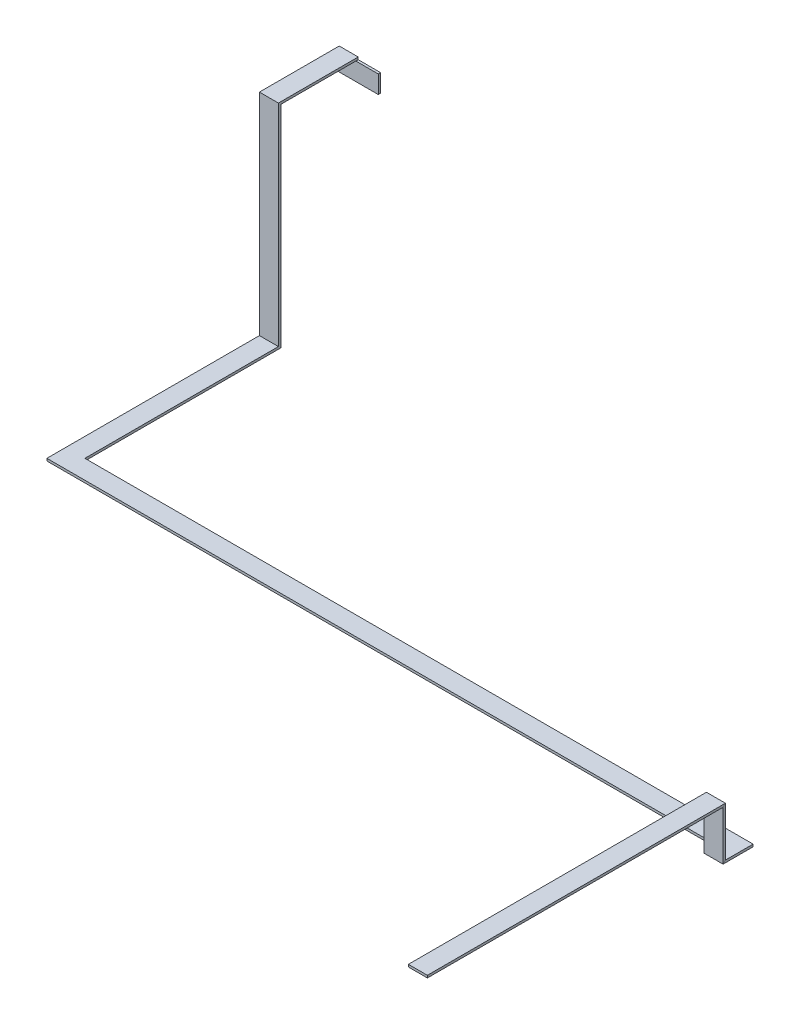
SolidWorks part; units mm, degrees
ref_plane "Alzado" through (0, 0, 0) normal (0, 0, 1) x (1, 0, 0)
ref_plane "Planta" through (0, 0, 0) normal (0, 1, 0) x (1, 0, 0)
ref_plane "Vista lateral" through (0, 0, 0) normal (1, 0, 0) x (0, 0, -1)
sketch "Croquis2" plane through (0, 0, 0) normal (0, 0, 1) x (1, 0, 0)
  line L1 (-25.4, 285.195) -> (25.4, 285.195)
  line L2 (-25.4, 285.195) -> (-25.4, -285.195)
  line L3 (-25.4, -285.195) -> (25.4, -285.195)
  line L4 (25.4, 285.195) -> (25.4, -285.195)
  line L5 (-25.4, 285.195) -> (25.4, -285.195) construction
  line L6 (-25.4, -285.195) -> (25.4, 285.195) construction
  point P0 (0, 0)
  dimension "D1" = 570.39
  dimension "D2" = 50.8
extrude "Saliente-Extruir1" add sketch "Croquis2" along normal blind 6.31
sketch "Croquis3" plane through (0, 0, 6.31) normal (0, 0, 1) x (1, 0, 0)
  line L1 (-25.4, -278.885) -> (25.4, -278.885)
  line L2 (-25.4, -278.885) -> (-25.4, -285.195)
  line L3 (-25.4, -285.195) -> (25.4, -285.195)
  line L4 (25.4, -278.885) -> (25.4, -285.195)
  line L5 (-25.4, -278.885) -> (25.4, -285.195) construction
  line L6 (-25.4, -285.195) -> (25.4, -278.885) construction
  point P0 (0, -282.04)
  dimension "D1" = 6.31
  dimension "D2" = 50.8
extrude "Saliente-Extruir2" add sketch "Croquis3" along normal blind 568.44
sketch "Croquis4" plane through (25.4, 0, 0) normal (1, 0, 0) x (0, 0, -1)
  line L1 (-523.95, -285.195) -> (-574.75, -285.195)
  line L2 (-523.95, -285.195) -> (-523.95, -278.885)
  line L3 (-523.95, -278.885) -> (-574.75, -278.885)
  line L4 (-574.75, -285.195) -> (-574.75, -278.885)
  line L5 (-523.95, -285.195) -> (-574.75, -278.885) construction
  line L6 (-523.95, -278.885) -> (-574.75, -285.195) construction
  point P0 (-549.35, -282.04)
  dimension "D1" = 50.8
extrude "Saliente-Extruir3" add sketch "Croquis4" along normal blind 1787.3
sketch "Croquis6" plane through (0, 0, 0) normal (0, 0, -1) x (-1, 0, 0)
  line L1 (-25.4, 278.885) -> (25.4, 278.885)
  line L2 (-25.4, 278.885) -> (-25.4, 285.195)
  line L3 (-25.4, 285.195) -> (25.4, 285.195)
  line L4 (25.4, 278.885) -> (25.4, 285.195)
  line L5 (-25.4, 278.885) -> (25.4, 285.195) construction
  line L6 (-25.4, 285.195) -> (25.4, 278.885) construction
  point P0 (0, 282.04)
  dimension "D1" = 6.31
  dimension "D2" = 50.8
sketch3d "Croquis3D2"
  line L0 (0, 282.04, 0) -> (0, 282.04, -204)
  line L1 (0, 282.04, -204) -> (0, 231.24, -204)
  dimension "D1" = 204
  dimension "D2" = 50.8
sweep "Barrer1" add profiles "Croquis6" path "Croquis3D2"
sketch "Croquis7" plane through (0, 0, -207.155) normal (0, 0, -1) x (-1, 0, 0)
  line L0 (-25.4, 231.24) -> (-85.4, 231.24)
  line L1 (-85.4, 231.24) -> (-85.4, 285.195)
  line L2 (-85.4, 285.195) -> (-25.4, 285.195)
  line L3 (-25.4, 285.195) -> (-25.4, 231.24)
  dimension "D1" = 60
extrude "Saliente-Extruir4" add sketch "Croquis7" against normal blind 6.31
sketch "Croquis8" plane through (0, 0, -200.845) normal (0, 0, 1) x (1, 0, 0)
  line L0 (25.4, 278.885) -> (25.4, 285.195)
  line L1 (25.4, 285.195) -> (85.4, 285.195)
  line L2 (85.4, 285.195) -> (85.4, 278.885)
  line L3 (85.4, 285.195) -> (85.4, 231.24) construction
  line L4 (85.4, 278.885) -> (25.4, 278.885)
extrude "Cortar-Extruir1" cut sketch "Croquis8" against normal blind 6.31
sketch "Croquis9" plane through (0, 0, 574.75) normal (0, 0, 1) x (1, 0, 0)
  line L0 (1812.7, -278.885) -> (-25.4, -278.885) construction
  line L1 (1761.9, -278.885) -> (1812.7, -278.885)
  line L2 (1761.9, -278.885) -> (1761.9, -285.195)
  line L3 (1761.9, -285.195) -> (1812.7, -285.195)
  line L4 (1812.7, -278.885) -> (1812.7, -285.195)
  line L5 (1761.9, -278.885) -> (1812.7, -285.195) construction
  line L6 (1761.9, -285.195) -> (1812.7, -278.885) construction
  point P0 (1787.3, -282.04)
  dimension "D1" = 50.8
sketch3d "Croquis3D3"
  line L0 (1787.3, -282.04, 574.75) -> (1787.3, -282.04, 601.16)
  line L1 (1787.3, -282.04, 601.16) -> (1787.3, -150.28, 601.16)
  line L2 (1787.3, -150.28, 601.16) -> (1787.3, -150.28, 1395.16)
  dimension "D1" = 26.41
  dimension "D2" = 131.76
  dimension "D3" = 794
sweep "Barrer2" add profiles "Croquis9" path "Croquis3D3"
